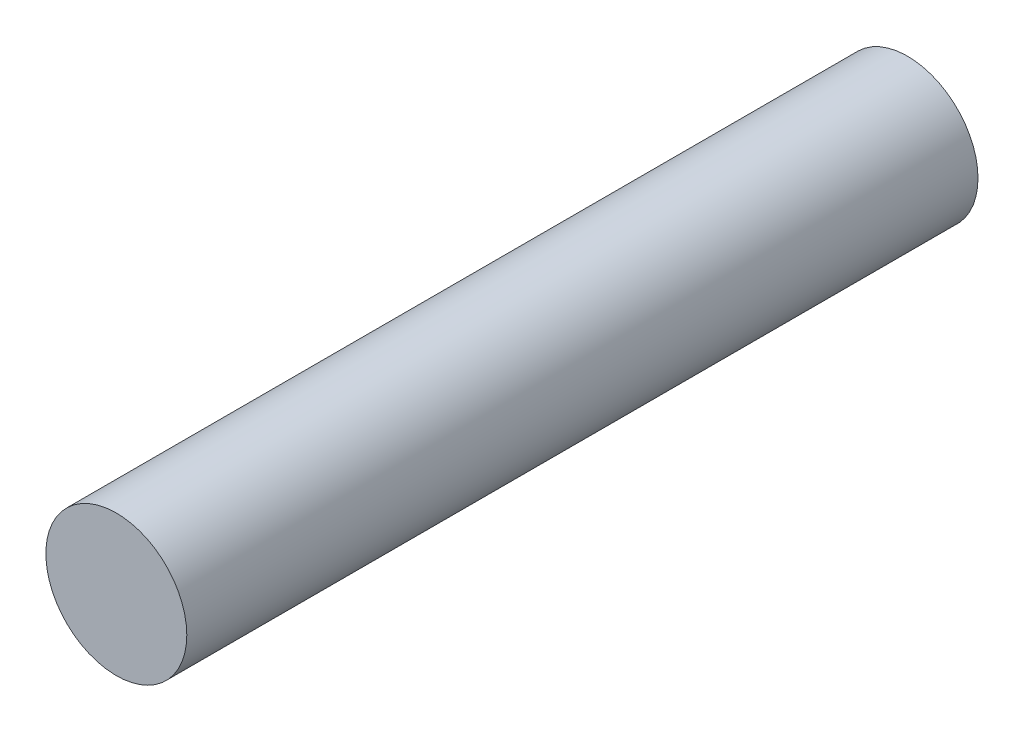
SolidWorks part; units mm, degrees
ref_plane "Alzado" through (0, 0, 0) normal (0, 0, 1) x (1, 0, 0)
ref_plane "Planta" through (0, 0, 0) normal (0, 1, 0) x (1, 0, 0)
ref_plane "Vista lateral" through (0, 0, 0) normal (1, 0, 0) x (0, 0, -1)
sketch "Croquis1" plane through (0, 0, 0) normal (0, 0, 1) x (1, 0, 0)
  circle A0 centre (0, 0) radius 1.75
  dimension "D1" = 3.5
extrude "Saliente-Extruir1" add sketch "Croquis1" along normal blind 19.65
